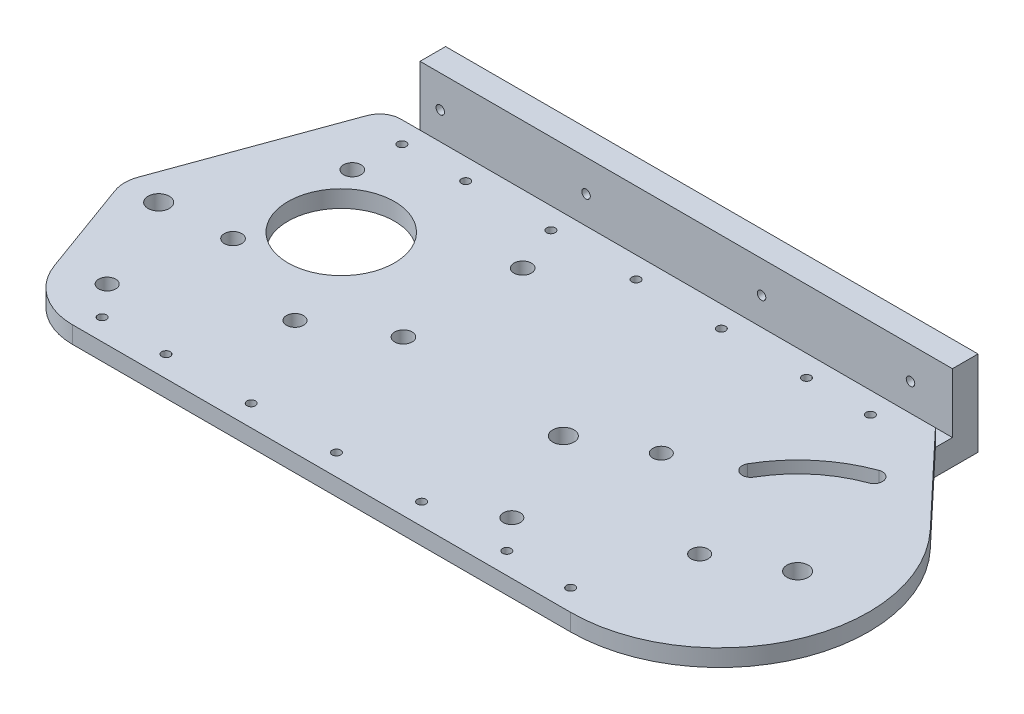
SolidWorks part; units mm, degrees
ref_plane "前视基准面" through (0, 0, 0) normal (0, 0, 1) x (1, 0, 0)
ref_plane "上视基准面" through (0, 0, 0) normal (0, 1, 0) x (1, 0, 0)
ref_plane "右视基准面" through (0, 0, 0) normal (1, 0, 0) x (0, 0, -1)
sketch "草图1" plane through (0, 0, 0) normal (0, 1, 0) x (1, 0, 0)
  line L0 (-95, 0) -> (0, 0) construction
  line L1 (0, 8.8147) -> (0, -8) construction
  line L2 (-95, 0) -> (-115, -34.641) construction
  line L3 (0, 0) -> (95, 0) construction
  line L4 (95, 0) -> (75, -34.641) construction
  line L5 (40, -8) -> (0, -8) construction
  line L6 (-102.5175, -2.7362) -> (-94.3667, -25.1303)
  line L7 (-80.2714, -35) -> (36.6801, -35)
  line L8 (-82, 29.134) -> (-129.5, -20.866) construction
  line L9 (-115, -34.641) -> (75, -34.641) construction
  line L10 (-115, -54.641) -> (75, -54.641) construction
  line L11 (-67.5, -34.641) -> (-67.5, 15.359) construction
  line L12 (-102.5175, 2.7362) -> (-88.2015, 42.0691)
  line L13 (-83.5031, 45.359) -> (42, 45.359)
  line L14 (-60.8782, 34.231) -> (81.6218, -15.769) construction
  line L15 (-88, 35.359) -> (-88, -4.641) construction
  line L16 (-88, -4.641) -> (-29.8, -4.641) construction
  line L17 (-29.8, -4.641) -> (-29.8, 35.359) construction
  line L18 (-29.8, 35.359) -> (-88, 35.359) construction
  line L19 (-67.5, 15.359) -> (-88, 15.359) construction
  line L20 (-78.9, 29.359) -> (-38.9, 29.359) construction
  line L21 (-38.9, 29.359) -> (-38.9, 1.359) construction
  line L22 (-78.9, 1.359) -> (-38.9, 1.359) construction
  line L23 (-78.9, 1.359) -> (-78.9, 29.359) construction
  line L24 (-67.5, 15.359) -> (-38.9, 15.359) construction
  line L25 (-55, -8) -> (-95, -8) construction
  line L26 (42, 45.359) -> (62.1355, 24.0212)
  line L27 (-95, -8) -> (-95, 0) construction
  line L28 (75, -34.641) -> (55, 0) construction
  line L29 (-95, 0) -> (-84.4345, -22.6577) construction
  line L30 (0, 0) -> (-15.8661, -27.4809) construction
  line L31 (0, 0) -> (10.5655, -22.6577) construction
  line L32 (55, 0) -> (40, 25.9808) construction
  line L33 (55, 0) -> (55, 8) construction
  line L34 (55, 8) -> (15, 8) construction
  line L35 (55, 0) -> (44.7394, 28.1908) construction
  line L36 (55, 0) -> (29.0192, 15) construction
  circle A0 centre (-95, 0) radius 2.5
  circle A1 centre (0, 0) radius 2.5
  circle A2 centre (-84.4345, -22.6577) radius 2
  arc A3 (-102.5175, 2.7362) -> (-102.5175, -2.7362) centre (-95, 0) ccw
  circle A4 centre (-67.5, 15.359) radius 20 construction
  circle A5 centre (-78.9, 29.359) radius 2.05
  circle A6 centre (-38.9, 29.359) radius 2.05
  arc A7 (-80.2714, -35) -> (-94.3667, -25.1303) centre (-80.2714, -20) cw
  circle A8 centre (-55, -8) radius 2
  circle A9 centre (40, -8) radius 2
  circle A10 centre (-115, -34.641) radius 20 construction
  circle A11 centre (75, -34.641) radius 20 construction
  circle A12 centre (-67.5, 15.359) radius 12.5
  circle A13 centre (-38.9, 1.359) radius 2.05
  circle A14 centre (-78.9, 1.359) radius 2.05
  arc A15 (-83.5031, 45.359) -> (-88.2015, 42.0691) centre (-83.5031, 40.359) ccw
  circle A16 centre (55, 0) radius 2.5
  arc A17 (36.6801, -35) -> (62.1355, 24.0212) centre (36.6801, 0) ccw
  circle A18 centre (10.5655, -22.6577) radius 2
  circle A19 centre (40, 25.9808) radius 2 construction
  circle A20 centre (15, 8) radius 2
  circle A21 centre (-78.2714, -30) radius 1
  circle A22 centre (-43.2714, -30) radius 1
  circle A23 centre (-3.2714, -30) radius 1
  arc A24 (45.4234, 26.3114) -> (44.0554, 30.0702) centre (44.7394, 28.1908) ccw
  arc A25 (27.2872, 16) -> (30.7513, 14) centre (29.0192, 15) ccw
  arc A26 (45.4234, 26.3114) -> (30.7513, 14) centre (55, 0) ccw
  arc A27 (46.6405, 28.8118) -> (28.0775, 13.2356) centre (55, 0) ccw construction
  arc A28 (44.0554, 30.0702) -> (27.2872, 16) centre (55, 0) ccw
  circle A29 centre (31.7286, -30) radius 1
  circle A30 centre (-78.2714, 40.359) radius 1
  circle A31 centre (-43.2714, 40.359) radius 1
  circle A32 centre (-3.2714, 40.359) radius 1
  circle A33 centre (31.7286, 40.359) radius 1
  circle A34 centre (-63.2714, -30) radius 1
  circle A35 centre (-23.2714, -30) radius 1
  circle A36 centre (16.7286, -30) radius 1
  circle A37 centre (-63.2714, 40.359) radius 1
  circle A38 centre (-23.2714, 40.359) radius 1
  circle A39 centre (16.7286, 40.359) radius 1
  dimension "D1" = 5
  dimension "D3" = 16
  dimension "D6" = 95
  dimension "D7" = 15
  dimension "D8" = 4
  dimension "D9" = 8
  dimension "D10" = 40
  dimension "D13" = 40
  dimension "D18" = 25
  dimension "D11" = 40
  dimension "D25" = 4.1
  dimension "D28" = 5
  dimension "D31" = 25
  dimension "D33" = 4
  dimension "D37" = 4
  dimension "D39" = 2
  dimension "D43" = 30
  dimension "D44" = 28
  dimension "D45" = 32
  dimension "D46" = 2
  dimension "D48" = 5
  dimension "D49" = 2
  dimension "D50" = 35
  dimension "D51" = 40
  dimension "D52" = 35
  dimension "D53" = 2
  dimension "D54" = 5
  dimension "D55" = 15
  dimension "D59" = 20
  dimension "D60" = 15
  dimension "D34" = 35
  dimension "D62" = 35
  dimension "D4" = 70
  dimension "D5" = 35
  dimension "D12" = 190
  dimension "D14" = 60
  dimension "D15" = 40
  dimension "D16" = 50
  dimension "D17" = 47.5
  dimension "D19" = 40
  dimension "D20" = 58.2
  dimension "D21" = 20.5
  dimension "D22" = 9.1
  dimension "D23" = 28
  dimension "D24" = 40
  dimension "D26" = 20
  dimension "D27" = 110
  dimension "D29" = 130
  dimension "D30" = 25
  dimension "D32" = 60
  dimension "D35" = 25
  dimension "D36" = 25
  dimension "D38" = 30
  dimension "D40" = 8
  dimension "D41" = 30
  dimension "D42" = 10
  dimension "D47" = 2
  dimension "D61" = 40
  dimension "D56" = 2
  dimension "D57" = 2
  dimension "D58" = 2
extrude "凸台-拉伸1" add sketch "草图1" along normal mid plane 4
scale "Scale1" scale about centroid uniform scaling yes scale factor 2
ref_plane "Plane1" through (98.7018, -4, -86.6963) normal (-1, 0, 0) x (0, 0, 1)
sketch "Sketch4" plane through (98.7018, -4, -86.6963) normal (-1, 0, 0) x (0, 0, 1)
  line L0 (-8, 0) -> (20, 0)
  line L1 (20, 0) -> (20, -12)
  line L2 (20, -12) -> (-20, -12)
  line L3 (-20, -12) -> (-20, 28)
  line L4 (-20, 28) -> (-8, 28)
  line L5 (-8, 0) -> (-8, 28)
  dimension "D1" = 12
  dimension "D2" = 40
  dimension "D3" = 20
  dimension "D4" = 12
  dimension "D5" = 40
extrude "Extrude2" add sketch "Sketch4" along normal blind 250
sketch "Sketch5" plane through (0, -16, 0) normal (0, -1, 0) x (1, 0, 0)
  circle A0 centre (8.1591, -76.6963) radius 2 construction
  circle A1 centre (-71.8409, -76.6963) radius 2 construction
  circle A2 centre (78.1591, -76.6963) radius 2 construction
  circle A3 centre (-141.8409, -76.6963) radius 2 construction
  circle A4 centre (8.1591, -76.6963) radius 2
  circle A5 centre (-71.8409, -76.6963) radius 2
  circle A6 centre (78.1591, -76.6963) radius 2
  circle A7 centre (-141.8409, -76.6963) radius 2
extrude "Extrude3" cut sketch "Sketch5" against normal through all
sketch "Sketch6" plane through (0, 0, -106.6963) normal (0, 0, -1) x (-1, 0, 0)
  line L0 (151.2982, 24) -> (-98.7018, 24) construction
  circle A0 centre (-79.0063, 9) radius 2
  circle A1 centre (-9.0598, 9) radius 2
  circle A2 centre (73.3433, 9) radius 2
  circle A3 centre (141.789, 9) radius 2
  point P8 (0, 0)
  point P13 (0, 0)
  dimension "D1" = 4
  dimension "D2" = 15
extrude "Extrude4" cut sketch "Sketch6" against normal through all
ref_plane "Plane2" through (0, 0, -6.3373) normal (0, 0, -1) x (-1, 0, 0)
